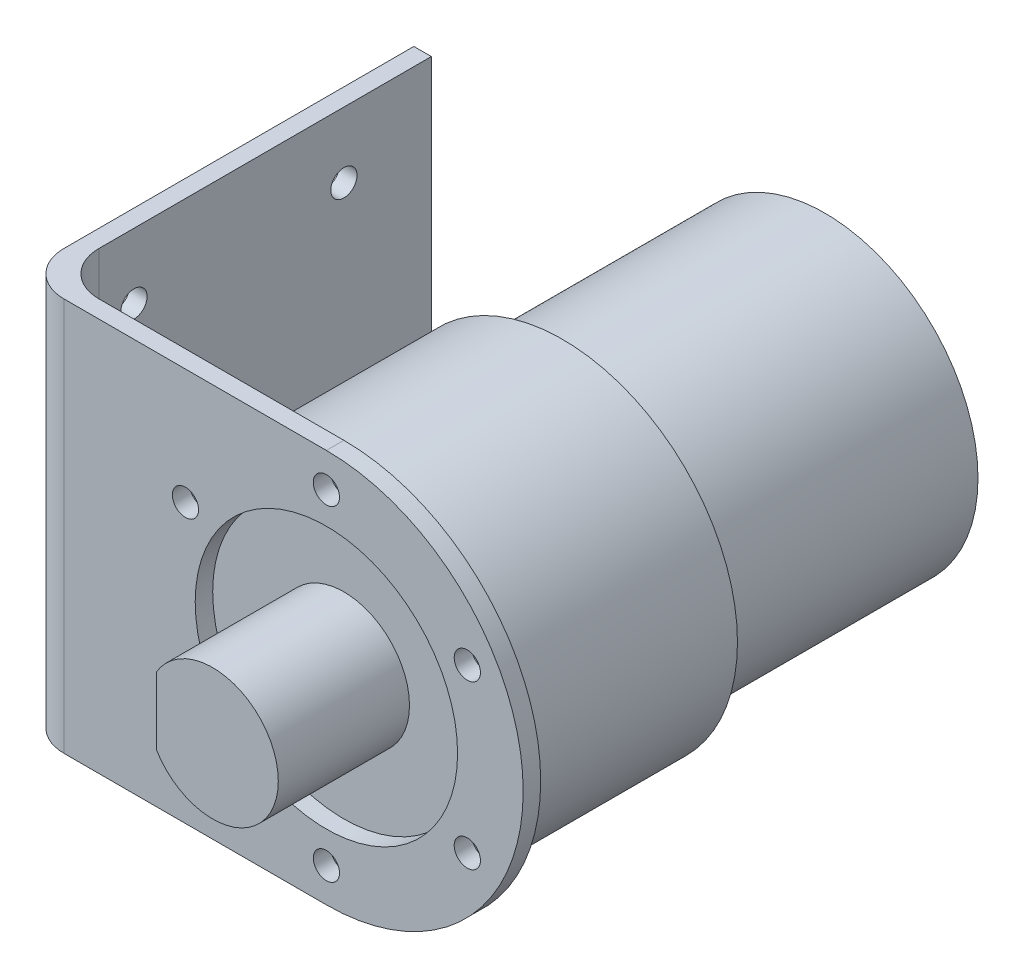
SolidWorks part; units mm, degrees
ref_plane "前视基准面" through (0, 0, 0) normal (0, 0, 1) x (1, 0, 0)
ref_plane "上视基准面" through (0, 0, 0) normal (0, 1, 0) x (1, 0, 0)
ref_plane "右视基准面" through (0, 0, 0) normal (1, 0, 0) x (0, 0, -1)
sketch "草图1" plane through (0, 0, 0) normal (0, 0, 1) x (1, 0, 0)
  circle A0 centre (0, 0) radius 17.5
  dimension "D1" = 35
extrude "凸台-拉伸1" add sketch "草图1" along normal blind 30
sketch "草图2" plane through (0, 0, 30) normal (0, 0, 1) x (1, 0, 0)
  circle A0 centre (0, 0) radius 20
  dimension "D1" = 40
extrude "凸台-拉伸2" add sketch "草图2" along normal blind 25
sketch "草图6" plane through (0, 0, 55) normal (0, 0, 1) x (1, 0, 0)
  line L0 (0, 22.5) -> (-35, 22.5)
  line L1 (-35, 22.5) -> (-35, -22.5)
  line L2 (-35, -22.5) -> (0, -22.5)
  arc A0 (0, -22.5) -> (0, 22.5) centre (0, 0) ccw
  dimension "D1" = 45
  dimension "D2" = 35
extrude "凸台-拉伸5" add sketch "草图6" along normal blind 2
sketch "草图7" plane through (0, 0, 57) normal (0, 0, 1) x (1, 0, 0)
  line L0 (-35, 22.5) -> (-33, 22.5)
  line L1 (0, 22.5) -> (-35, 22.5) construction
  line L2 (-33, 22.5) -> (-33, -22.5)
  line L3 (-35, -22.5) -> (0, -22.5) construction
  line L4 (-33, -22.5) -> (-35, -22.5)
  line L5 (-35, -22.5) -> (-35, 22.5)
  dimension "D1" = 2
extrude "凸台-拉伸6" add sketch "草图7" against normal blind 45
fillet "圆角3" radius 5 2 edges at (-33, 0, 55) (-35, 0, 57)
sketch "草图8" plane through (-35, 0, 0) normal (-1, 0, 0) x (0, 0, 1)
  line L0 (26.8962, 0) -> (47.9887, 0) construction
  line L1 (12, 22.5) -> (12, -22.5) construction
  circle A0 centre (22, 15) radius 1.5
  circle A1 centre (22, -15) radius 1.5
  circle A2 centre (46, 15) radius 1.5
  circle A3 centre (46, -15) radius 1.5
  dimension "D1" = 3
  dimension "D2" = 30
  dimension "D3" = 3
  dimension "D4" = 24
  dimension "D5" = 10
extrude "切除-拉伸1" cut sketch "草图8" against normal blind 5
sketch "草图9" plane through (0, 0, 55) normal (0, 0, -1) x (-1, 0, 0)
  circle A0 centre (0, 0) radius 15
  dimension "D1" = 30
extrude "切除-拉伸2" cut sketch "草图9" against normal blind 10
sketch "草图10" plane through (0, 0, 0) normal (0, 0, -1) x (-1, 0, 0)
  line L0 (6.4409, 3.8425) -> (6.4409, -3.8425)
  arc A0 (6.4409, 3.8425) -> (6.4409, -3.8425) centre (0, 0) ccw
  dimension "D1" = 15
extrude "凸台-拉伸7" add sketch "草图10" against normal blind 70
sketch "草图11" plane through (0, 0, 57) normal (0, 0, 1) x (1, 0, 0)
  circle A0 centre (0, 0) radius 18.6051 construction
  circle A1 centre (0, 18.6051) radius 1.5
  circle A2 centre (16.1124, 9.3025) radius 1.5
  circle A3 centre (16.1124, -9.3025) radius 1.5
  circle A4 centre (0, -18.6051) radius 1.5
  circle A5 centre (-16.1124, -9.3025) radius 1.5
  circle A6 centre (-16.1124, 9.3025) radius 1.5
  point P17 (0, 0)
  dimension "D1" = 3
  dimension "D2" = 6
extrude "切除-拉伸3" cut sketch "草图11" against normal blind 2
